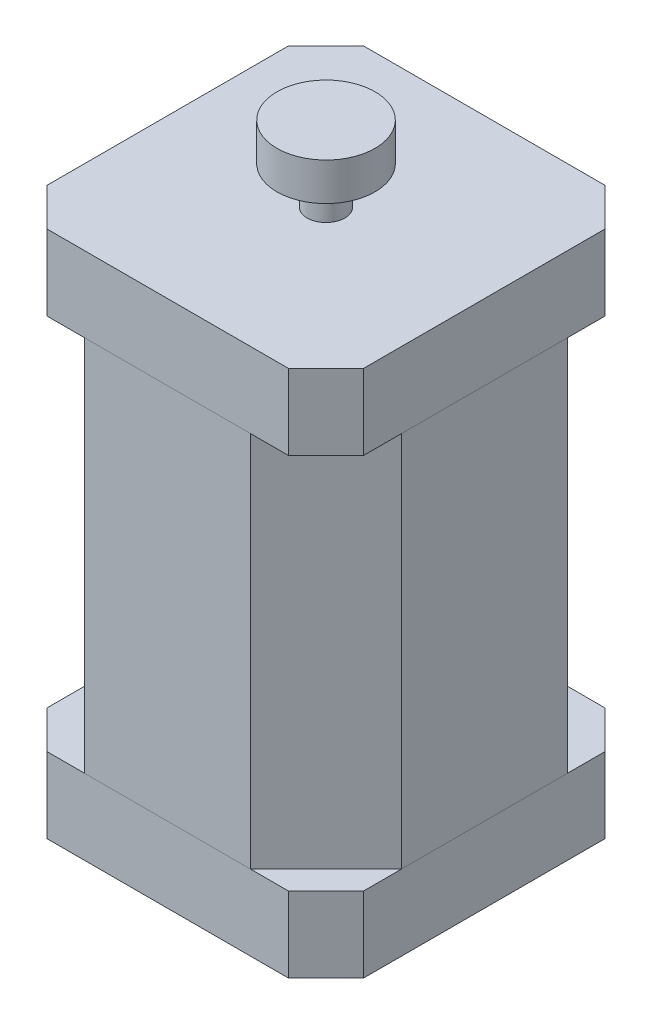
SolidWorks part; units mm, degrees
ref_plane "前基準面" through (0, 0, 0) normal (0, 0, 1) x (1, 0, 0)
ref_plane "上基準面" through (0, 0, 0) normal (0, 1, 0) x (1, 0, 0)
ref_plane "右基準面" through (0, 0, 0) normal (1, 0, 0) x (0, 0, -1)
sketch "草圖1" plane through (0, 0, 0) normal (0, 0, 1) x (1, 0, 0)
  line L0 (0, 0) -> (42, 0) construction
  line L2 (0, 0) -> (42, 0)
  line L3 (0, 0) -> (0, 50)
  line L4 (0, 50) -> (42, 50)
  line L5 (42, 0) -> (42, 50)
  dimension "D1" = 42
  dimension "D2" = 50
extrude "填料-伸長1" add sketch "草圖1" along normal blind 42
chamfer "導角1" distance 10 angle 45 4 edges at (0, 25, 0) (42, 25, 0) (0, 25, 42) (42, 25, 42)
sketch "草圖2" plane through (0, 50, 0) normal (0, 1, 0) x (1, 0, 0)
  line L0 (0, -32) -> (0, -43.9776) construction
  line L1 (10, -42) -> (-3.9932, -42) construction
  line L3 (0, -42) -> (42, -42)
  line L4 (0, -42) -> (0, 0)
  line L5 (0, 0) -> (42, 0)
  line L6 (42, -42) -> (42, 0)
  dimension "D1" = 42
  dimension "D2" = 42
extrude "填料-伸長2" add sketch "草圖2" along normal blind 10 separate body
sketch "草圖3" plane through (0, 0, 0) normal (0, -1, 0) x (1, 0, 0)
  line L1 (0, 0) -> (42, 0)
  line L2 (0, 0) -> (0, 42)
  line L3 (0, 42) -> (42, 42)
  line L4 (42, 0) -> (42, 42)
extrude "填料-伸長3" add sketch "草圖3" along normal blind 10 separate body
chamfer "導角2" distance 5 angle 45 4 edges at (42, 55, 0) (0, 55, 42) (0, 55, 0) (42, 55, 42)
chamfer "導角3" distance 5 angle 45 4 edges at (0, -5, 0) (0, -5, 42) (42, -5, 0) (42, -5, 42)
sketch "草圖4" plane through (0, 60, 0) normal (0, 1, 0) x (1, 0, 0)
  line L0 (39.5, -2.5) -> (2.5, -39.5) construction
  line L1 (42, -5) -> (37, 0) construction
  line L2 (0, -37) -> (5, -42) construction
  circle A0 centre (21, -21) radius 2.5
  dimension "D1" = 5
extrude "填料-伸長4" add sketch "草圖4" along normal blind 10
sketch "草圖5" plane through (0, 70, 0) normal (0, 1, 0) x (1, 0, 0)
  circle A0 centre (21, -21) radius 6.5
  dimension "D1" = 13
extrude "填料-伸長5" add sketch "草圖5" against normal blind 5
